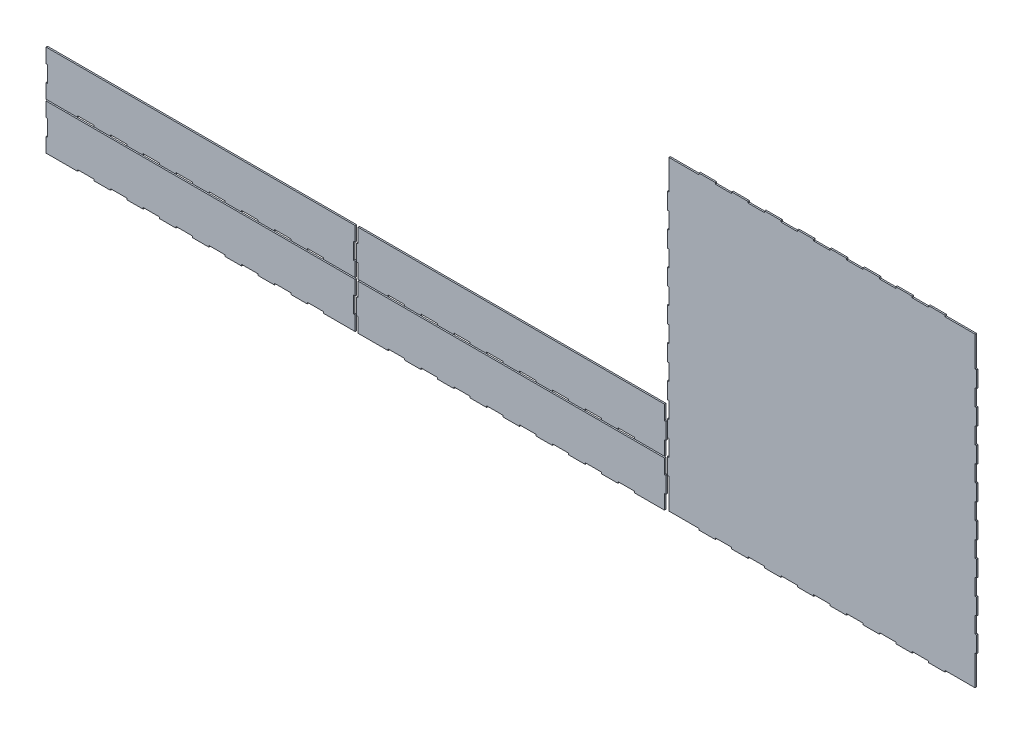
SolidWorks part; units mm, degrees
ref_plane "Front Plane" through (0, 0, 0) normal (0, 0, 1) x (1, 0, 0)
ref_plane "Top Plane" through (0, 0, 0) normal (0, 1, 0) x (1, 0, 0)
ref_plane "Right Plane" through (0, 0, 0) normal (1, 0, 0) x (0, 0, -1)
sketch "Model" plane through (0, 0, 0) normal (0, 0, 1) x (1, 0, 0)
  line L0 (0, 96) -> (0, 66.375)
  line L1 (0, 66.375) -> (3, 66.375)
  line L2 (3, 66.375) -> (3, 32.625)
  line L3 (3, 32.625) -> (0, 32.625)
  line L4 (0, 32.625) -> (0, 3)
  line L5 (0, 3) -> (64.875, 3)
  line L6 (64.875, 3) -> (64.875, 6)
  line L7 (64.875, 6) -> (98.625, 6)
  line L8 (98.625, 6) -> (98.625, 3)
  line L9 (98.625, 3) -> (132.375, 3)
  line L10 (132.375, 3) -> (132.375, 6)
  line L11 (132.375, 6) -> (166.125, 6)
  line L12 (166.125, 6) -> (166.125, 3)
  line L13 (166.125, 3) -> (199.875, 3)
  line L14 (199.875, 3) -> (199.875, 6)
  line L15 (199.875, 6) -> (233.625, 6)
  line L16 (233.625, 6) -> (233.625, 3)
  line L17 (233.625, 3) -> (267.375, 3)
  line L18 (267.375, 3) -> (267.375, 6)
  line L19 (267.375, 6) -> (301.125, 6)
  line L20 (301.125, 6) -> (301.125, 3)
  line L21 (301.125, 3) -> (334.875, 3)
  line L22 (334.875, 3) -> (334.875, 6)
  line L23 (334.875, 6) -> (368.625, 6)
  line L24 (368.625, 6) -> (368.625, 3)
  line L25 (368.625, 3) -> (402.375, 3)
  line L26 (402.375, 3) -> (402.375, 6)
  line L27 (402.375, 6) -> (436.125, 6)
  line L28 (436.125, 6) -> (436.125, 3)
  line L29 (436.125, 3) -> (469.875, 3)
  line L30 (469.875, 3) -> (469.875, 6)
  line L31 (469.875, 6) -> (503.625, 6)
  line L32 (503.625, 6) -> (503.625, 3)
  line L33 (503.625, 3) -> (537.375, 3)
  line L34 (537.375, 3) -> (537.375, 6)
  line L35 (537.375, 6) -> (571.125, 6)
  line L36 (571.125, 6) -> (571.125, 3)
  line L37 (571.125, 3) -> (604.875, 3)
  line L38 (604.875, 3) -> (636, 3)
  line L39 (636, 3) -> (636, 32.625)
  line L40 (636, 32.625) -> (633, 32.625)
  line L41 (633, 32.625) -> (633, 66.375)
  line L42 (633, 66.375) -> (636, 66.375)
  line L43 (636, 66.375) -> (636, 96)
  line L44 (636, 96) -> (0, 96)
  line L45 (642, 96) -> (642, 66.375)
  line L46 (642, 66.375) -> (639, 66.375)
  line L47 (639, 66.375) -> (639, 32.625)
  line L48 (639, 32.625) -> (642, 32.625)
  line L49 (642, 32.625) -> (642, 3)
  line L50 (642, 3) -> (703.875, 3)
  line L51 (703.875, 3) -> (703.875, 6)
  line L52 (703.875, 6) -> (737.625, 6)
  line L53 (737.625, 6) -> (737.625, 3)
  line L54 (737.625, 3) -> (771.375, 3)
  line L55 (771.375, 3) -> (771.375, 6)
  line L56 (771.375, 6) -> (805.125, 6)
  line L57 (805.125, 6) -> (805.125, 3)
  line L58 (805.125, 3) -> (838.875, 3)
  line L59 (838.875, 3) -> (838.875, 6)
  line L60 (838.875, 6) -> (872.625, 6)
  line L61 (872.625, 6) -> (872.625, 3)
  line L62 (872.625, 3) -> (906.375, 3)
  line L63 (906.375, 3) -> (906.375, 6)
  line L64 (906.375, 6) -> (940.125, 6)
  line L65 (940.125, 6) -> (940.125, 3)
  line L66 (940.125, 3) -> (973.875, 3)
  line L67 (973.875, 3) -> (973.875, 6)
  line L68 (973.875, 6) -> (1007.625, 6)
  line L69 (1007.625, 6) -> (1007.625, 3)
  line L70 (1007.625, 3) -> (1041.375, 3)
  line L71 (1041.375, 3) -> (1041.375, 6)
  line L72 (1041.375, 6) -> (1075.125, 6)
  line L73 (1075.125, 6) -> (1075.125, 3)
  line L74 (1075.125, 3) -> (1108.875, 3)
  line L75 (1108.875, 3) -> (1108.875, 6)
  line L76 (1108.875, 6) -> (1142.625, 6)
  line L77 (1142.625, 6) -> (1142.625, 3)
  line L78 (1142.625, 3) -> (1176.375, 3)
  line L79 (1176.375, 3) -> (1176.375, 6)
  line L80 (1176.375, 6) -> (1210.125, 6)
  line L81 (1210.125, 6) -> (1210.125, 3)
  line L82 (1210.125, 3) -> (1243.875, 3)
  line L83 (1243.875, 3) -> (1272, 3)
  line L84 (1272, 3) -> (1272, 32.625)
  line L85 (1272, 32.625) -> (1275, 32.625)
  line L86 (1275, 32.625) -> (1275, 66.375)
  line L87 (1275, 66.375) -> (1272, 66.375)
  line L88 (1272, 66.375) -> (1272, 96)
  line L89 (1272, 96) -> (642, 96)
  line L90 (0, 192) -> (0, 162.375)
  line L91 (0, 162.375) -> (3, 162.375)
  line L92 (3, 162.375) -> (3, 128.625)
  line L93 (3, 128.625) -> (0, 128.625)
  line L94 (0, 128.625) -> (0, 99)
  line L95 (0, 99) -> (64.875, 99)
  line L96 (64.875, 99) -> (64.875, 102)
  line L97 (64.875, 102) -> (98.625, 102)
  line L98 (98.625, 102) -> (98.625, 99)
  line L99 (98.625, 99) -> (132.375, 99)
  line L100 (132.375, 99) -> (132.375, 102)
  line L101 (132.375, 102) -> (166.125, 102)
  line L102 (166.125, 102) -> (166.125, 99)
  line L103 (166.125, 99) -> (199.875, 99)
  line L104 (199.875, 99) -> (199.875, 102)
  line L105 (199.875, 102) -> (233.625, 102)
  line L106 (233.625, 102) -> (233.625, 99)
  line L107 (233.625, 99) -> (267.375, 99)
  line L108 (267.375, 99) -> (267.375, 102)
  line L109 (267.375, 102) -> (301.125, 102)
  line L110 (301.125, 102) -> (301.125, 99)
  line L111 (301.125, 99) -> (334.875, 99)
  line L112 (334.875, 99) -> (334.875, 102)
  line L113 (334.875, 102) -> (368.625, 102)
  line L114 (368.625, 102) -> (368.625, 99)
  line L115 (368.625, 99) -> (402.375, 99)
  line L116 (402.375, 99) -> (402.375, 102)
  line L117 (402.375, 102) -> (436.125, 102)
  line L118 (436.125, 102) -> (436.125, 99)
  line L119 (436.125, 99) -> (469.875, 99)
  line L120 (469.875, 99) -> (469.875, 102)
  line L121 (469.875, 102) -> (503.625, 102)
  line L122 (503.625, 102) -> (503.625, 99)
  line L123 (503.625, 99) -> (537.375, 99)
  line L124 (537.375, 99) -> (537.375, 102)
  line L125 (537.375, 102) -> (571.125, 102)
  line L126 (571.125, 102) -> (571.125, 99)
  line L127 (571.125, 99) -> (604.875, 99)
  line L128 (604.875, 99) -> (636, 99)
  line L129 (636, 99) -> (636, 128.625)
  line L130 (636, 128.625) -> (633, 128.625)
  line L131 (633, 128.625) -> (633, 162.375)
  line L132 (633, 162.375) -> (636, 162.375)
  line L133 (636, 162.375) -> (636, 192)
  line L134 (636, 192) -> (0, 192)
  line L135 (642, 192) -> (642, 162.375)
  line L136 (642, 162.375) -> (639, 162.375)
  line L137 (639, 162.375) -> (639, 128.625)
  line L138 (639, 128.625) -> (642, 128.625)
  line L139 (642, 128.625) -> (642, 99)
  line L140 (642, 99) -> (703.875, 99)
  line L141 (703.875, 99) -> (703.875, 102)
  line L142 (703.875, 102) -> (737.625, 102)
  line L143 (737.625, 102) -> (737.625, 99)
  line L144 (737.625, 99) -> (771.375, 99)
  line L145 (771.375, 99) -> (771.375, 102)
  line L146 (771.375, 102) -> (805.125, 102)
  line L147 (805.125, 102) -> (805.125, 99)
  line L148 (805.125, 99) -> (838.875, 99)
  line L149 (838.875, 99) -> (838.875, 102)
  line L150 (838.875, 102) -> (872.625, 102)
  line L151 (872.625, 102) -> (872.625, 99)
  line L152 (872.625, 99) -> (906.375, 99)
  line L153 (906.375, 99) -> (906.375, 102)
  line L154 (906.375, 102) -> (940.125, 102)
  line L155 (940.125, 102) -> (940.125, 99)
  line L156 (940.125, 99) -> (973.875, 99)
  line L157 (973.875, 99) -> (973.875, 102)
  line L158 (973.875, 102) -> (1007.625, 102)
  line L159 (1007.625, 102) -> (1007.625, 99)
  line L160 (1007.625, 99) -> (1041.375, 99)
  line L161 (1041.375, 99) -> (1041.375, 102)
  line L162 (1041.375, 102) -> (1075.125, 102)
  line L163 (1075.125, 102) -> (1075.125, 99)
  line L164 (1075.125, 99) -> (1108.875, 99)
  line L165 (1108.875, 99) -> (1108.875, 102)
  line L166 (1108.875, 102) -> (1142.625, 102)
  line L167 (1142.625, 102) -> (1142.625, 99)
  line L168 (1142.625, 99) -> (1176.375, 99)
  line L169 (1176.375, 99) -> (1176.375, 102)
  line L170 (1176.375, 102) -> (1210.125, 102)
  line L171 (1210.125, 102) -> (1210.125, 99)
  line L172 (1210.125, 99) -> (1243.875, 99)
  line L173 (1243.875, 99) -> (1272, 99)
  line L174 (1272, 99) -> (1272, 128.625)
  line L175 (1272, 128.625) -> (1275, 128.625)
  line L176 (1275, 128.625) -> (1275, 162.375)
  line L177 (1275, 162.375) -> (1272, 162.375)
  line L178 (1272, 162.375) -> (1272, 192)
  line L179 (1272, 192) -> (642, 192)
  line L180 (1281, 636) -> (1281, 574.125)
  line L181 (1281, 574.125) -> (1278, 574.125)
  line L182 (1278, 574.125) -> (1278, 540.375)
  line L183 (1278, 540.375) -> (1281, 540.375)
  line L184 (1281, 540.375) -> (1281, 506.625)
  line L185 (1281, 506.625) -> (1278, 506.625)
  line L186 (1278, 506.625) -> (1278, 472.875)
  line L187 (1278, 472.875) -> (1281, 472.875)
  line L188 (1281, 472.875) -> (1281, 439.125)
  line L189 (1281, 439.125) -> (1278, 439.125)
  line L190 (1278, 439.125) -> (1278, 405.375)
  line L191 (1278, 405.375) -> (1281, 405.375)
  line L192 (1281, 405.375) -> (1281, 371.625)
  line L193 (1281, 371.625) -> (1278, 371.625)
  line L194 (1278, 371.625) -> (1278, 337.875)
  line L195 (1278, 337.875) -> (1281, 337.875)
  line L196 (1281, 337.875) -> (1281, 304.125)
  line L197 (1281, 304.125) -> (1278, 304.125)
  line L198 (1278, 304.125) -> (1278, 270.375)
  line L199 (1278, 270.375) -> (1281, 270.375)
  line L200 (1281, 270.375) -> (1281, 236.625)
  line L201 (1281, 236.625) -> (1278, 236.625)
  line L202 (1278, 236.625) -> (1278, 202.875)
  line L203 (1278, 202.875) -> (1281, 202.875)
  line L204 (1281, 202.875) -> (1281, 169.125)
  line L205 (1281, 169.125) -> (1278, 169.125)
  line L206 (1278, 169.125) -> (1278, 135.375)
  line L207 (1278, 135.375) -> (1281, 135.375)
  line L208 (1281, 135.375) -> (1281, 101.625)
  line L209 (1281, 101.625) -> (1278, 101.625)
  line L210 (1278, 101.625) -> (1278, 67.875)
  line L211 (1278, 67.875) -> (1281, 67.875)
  line L212 (1281, 67.875) -> (1281, 34.125)
  line L213 (1281, 34.125) -> (1281, 6)
  line L214 (1281, 6) -> (1342.875, 6)
  line L215 (1342.875, 6) -> (1342.875, 3)
  line L216 (1342.875, 3) -> (1376.625, 3)
  line L217 (1376.625, 3) -> (1376.625, 6)
  line L218 (1376.625, 6) -> (1410.375, 6)
  line L219 (1410.375, 6) -> (1410.375, 3)
  line L220 (1410.375, 3) -> (1444.125, 3)
  line L221 (1444.125, 3) -> (1444.125, 6)
  line L222 (1444.125, 6) -> (1477.875, 6)
  line L223 (1477.875, 6) -> (1477.875, 3)
  line L224 (1477.875, 3) -> (1511.625, 3)
  line L225 (1511.625, 3) -> (1511.625, 6)
  line L226 (1511.625, 6) -> (1545.375, 6)
  line L227 (1545.375, 6) -> (1545.375, 3)
  line L228 (1545.375, 3) -> (1579.125, 3)
  line L229 (1579.125, 3) -> (1579.125, 6)
  line L230 (1579.125, 6) -> (1612.875, 6)
  line L231 (1612.875, 6) -> (1612.875, 3)
  line L232 (1612.875, 3) -> (1646.625, 3)
  line L233 (1646.625, 3) -> (1646.625, 6)
  line L234 (1646.625, 6) -> (1680.375, 6)
  line L235 (1680.375, 6) -> (1680.375, 3)
  line L236 (1680.375, 3) -> (1714.125, 3)
  line L237 (1714.125, 3) -> (1714.125, 6)
  line L238 (1714.125, 6) -> (1747.875, 6)
  line L239 (1747.875, 6) -> (1747.875, 3)
  line L240 (1747.875, 3) -> (1781.625, 3)
  line L241 (1781.625, 3) -> (1781.625, 6)
  line L242 (1781.625, 6) -> (1815.375, 6)
  line L243 (1815.375, 6) -> (1815.375, 3)
  line L244 (1815.375, 3) -> (1849.125, 3)
  line L245 (1849.125, 3) -> (1849.125, 6)
  line L246 (1849.125, 6) -> (1882.875, 6)
  line L247 (1882.875, 6) -> (1911, 6)
  line L248 (1911, 6) -> (1911, 67.875)
  line L249 (1911, 67.875) -> (1914, 67.875)
  line L250 (1914, 67.875) -> (1914, 101.625)
  line L251 (1914, 101.625) -> (1911, 101.625)
  line L252 (1911, 101.625) -> (1911, 135.375)
  line L253 (1911, 135.375) -> (1914, 135.375)
  line L254 (1914, 135.375) -> (1914, 169.125)
  line L255 (1914, 169.125) -> (1911, 169.125)
  line L256 (1911, 169.125) -> (1911, 202.875)
  line L257 (1911, 202.875) -> (1914, 202.875)
  line L258 (1914, 202.875) -> (1914, 236.625)
  line L259 (1914, 236.625) -> (1911, 236.625)
  line L260 (1911, 236.625) -> (1911, 270.375)
  line L261 (1911, 270.375) -> (1914, 270.375)
  line L262 (1914, 270.375) -> (1914, 304.125)
  line L263 (1914, 304.125) -> (1911, 304.125)
  line L264 (1911, 304.125) -> (1911, 337.875)
  line L265 (1911, 337.875) -> (1914, 337.875)
  line L266 (1914, 337.875) -> (1914, 371.625)
  line L267 (1914, 371.625) -> (1911, 371.625)
  line L268 (1911, 371.625) -> (1911, 405.375)
  line L269 (1911, 405.375) -> (1914, 405.375)
  line L270 (1914, 405.375) -> (1914, 439.125)
  line L271 (1914, 439.125) -> (1911, 439.125)
  line L272 (1911, 439.125) -> (1911, 472.875)
  line L273 (1911, 472.875) -> (1914, 472.875)
  line L274 (1914, 472.875) -> (1914, 506.625)
  line L275 (1914, 506.625) -> (1911, 506.625)
  line L276 (1911, 506.625) -> (1911, 540.375)
  line L277 (1911, 540.375) -> (1914, 540.375)
  line L278 (1914, 540.375) -> (1914, 574.125)
  line L279 (1914, 574.125) -> (1911, 574.125)
  line L280 (1911, 574.125) -> (1911, 607.875)
  line L281 (1911, 607.875) -> (1911, 636)
  line L282 (1911, 636) -> (1849.125, 636)
  line L283 (1849.125, 636) -> (1849.125, 639)
  line L284 (1849.125, 639) -> (1815.375, 639)
  line L285 (1815.375, 639) -> (1815.375, 636)
  line L286 (1815.375, 636) -> (1781.625, 636)
  line L287 (1781.625, 636) -> (1781.625, 639)
  line L288 (1781.625, 639) -> (1747.875, 639)
  line L289 (1747.875, 639) -> (1747.875, 636)
  line L290 (1747.875, 636) -> (1714.125, 636)
  line L291 (1714.125, 636) -> (1714.125, 639)
  line L292 (1714.125, 639) -> (1680.375, 639)
  line L293 (1680.375, 639) -> (1680.375, 636)
  line L294 (1680.375, 636) -> (1646.625, 636)
  line L295 (1646.625, 636) -> (1646.625, 639)
  line L296 (1646.625, 639) -> (1612.875, 639)
  line L297 (1612.875, 639) -> (1612.875, 636)
  line L298 (1612.875, 636) -> (1579.125, 636)
  line L299 (1579.125, 636) -> (1579.125, 639)
  line L300 (1579.125, 639) -> (1545.375, 639)
  line L301 (1545.375, 639) -> (1545.375, 636)
  line L302 (1545.375, 636) -> (1511.625, 636)
  line L303 (1511.625, 636) -> (1511.625, 639)
  line L304 (1511.625, 639) -> (1477.875, 639)
  line L305 (1477.875, 639) -> (1477.875, 636)
  line L306 (1477.875, 636) -> (1444.125, 636)
  line L307 (1444.125, 636) -> (1444.125, 639)
  line L308 (1444.125, 639) -> (1410.375, 639)
  line L309 (1410.375, 639) -> (1410.375, 636)
  line L310 (1410.375, 636) -> (1376.625, 636)
  line L311 (1376.625, 636) -> (1376.625, 639)
  line L312 (1376.625, 639) -> (1342.875, 639)
  line L313 (1342.875, 639) -> (1342.875, 636)
  line L314 (1342.875, 636) -> (1309.125, 636)
  line L315 (1309.125, 636) -> (1281, 636)
extrude "Boss-Extrude1" add sketch "Model" along normal blind 3
